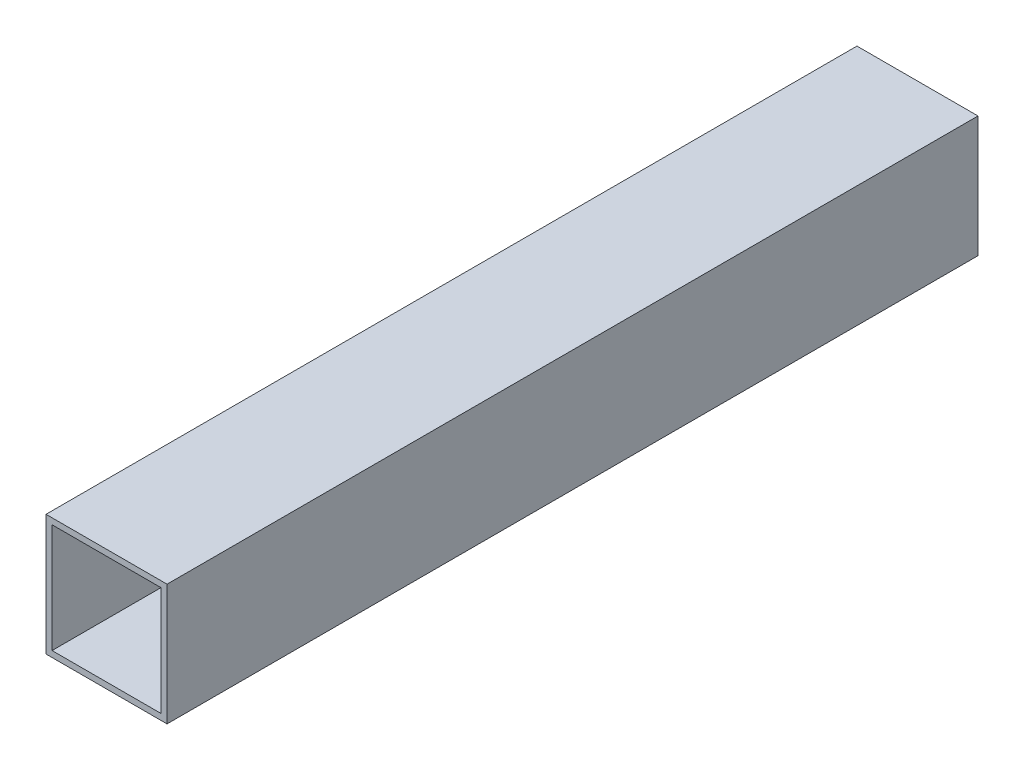
SolidWorks part; units mm, degrees
ref_plane "Alzado" through (0, 0, 0) normal (0, 0, 1) x (1, 0, 0)
ref_plane "Planta" through (0, 0, 0) normal (0, 1, 0) x (1, 0, 0)
ref_plane "Vista lateral" through (0, 0, 0) normal (1, 0, 0) x (0, 0, -1)
sketch "Croquis1" plane through (0, 0, 0) normal (0, 0, 1) x (1, 0, 0)
  line L1 (20, -20) -> (-20, -20)
  line L2 (20, -20) -> (20, 20)
  line L3 (20, 20) -> (-20, 20)
  line L4 (-20, -20) -> (-20, 20)
  line L5 (20, -20) -> (-20, 20) construction
  line L6 (20, 20) -> (-20, -20) construction
  point P0 (0, 0)
  dimension "D1" = 40
  dimension "D2" = 40
extrude "Extruir-Lámina1" add sketch "Croquis1" along normal blind 268 thin
